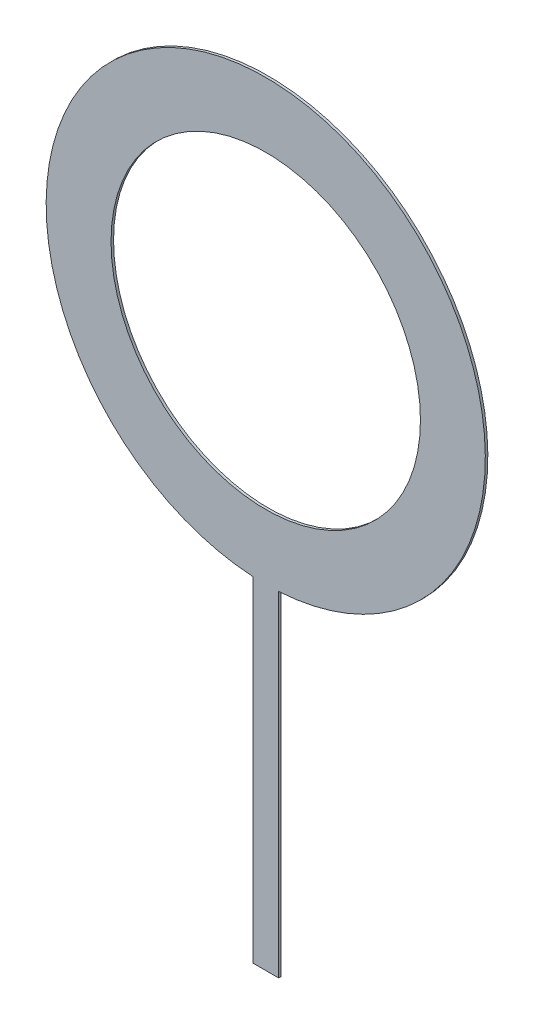
SolidWorks part; units mm, degrees
material "Brass"
ref_plane "Front" through (0, 0, 0) normal (0, 0, 1) x (1, 0, 0)
ref_plane "Top" through (0, 0, 0) normal (0, 1, 0) x (1, 0, 0)
ref_plane "Right" through (0, 0, 0) normal (1, 0, 0) x (0, 0, -1)
sketch "Sketch1" plane through (0, 0, 0) normal (0, 0, 1) x (1, 0, 0)
  line L0 (0, -7.75) -> (0, -27.75)
  line L2 (-0.65, -27.75) -> (0.65, -27.75)
  line L3 (-0.65, -27.75) -> (-0.65, -7.75)
  line L4 (-0.65, -7.75) -> (0.65, -7.75)
  line L5 (0.65, -27.75) -> (0.65, -7.75)
  circle A0 centre (0, 0) radius 11
  circle A1 centre (0, 0) radius 7.75
  point P10 (0, -7.75)
  point P13 (0, -27.75)
  dimension "D1" = 22
  dimension "D2" = 15.5
  dimension "D3" = 1.3
  dimension "D4" = 20
extrude "Boss-Extrude1" add sketch "Sketch1" along normal blind 0.127 contours L4 A1 L5 A0 L3 | L0 A0 L5 L4 | L3 A0 L0 L4 | A0 L3 L2 L0 | A0 L0 L2 L5
